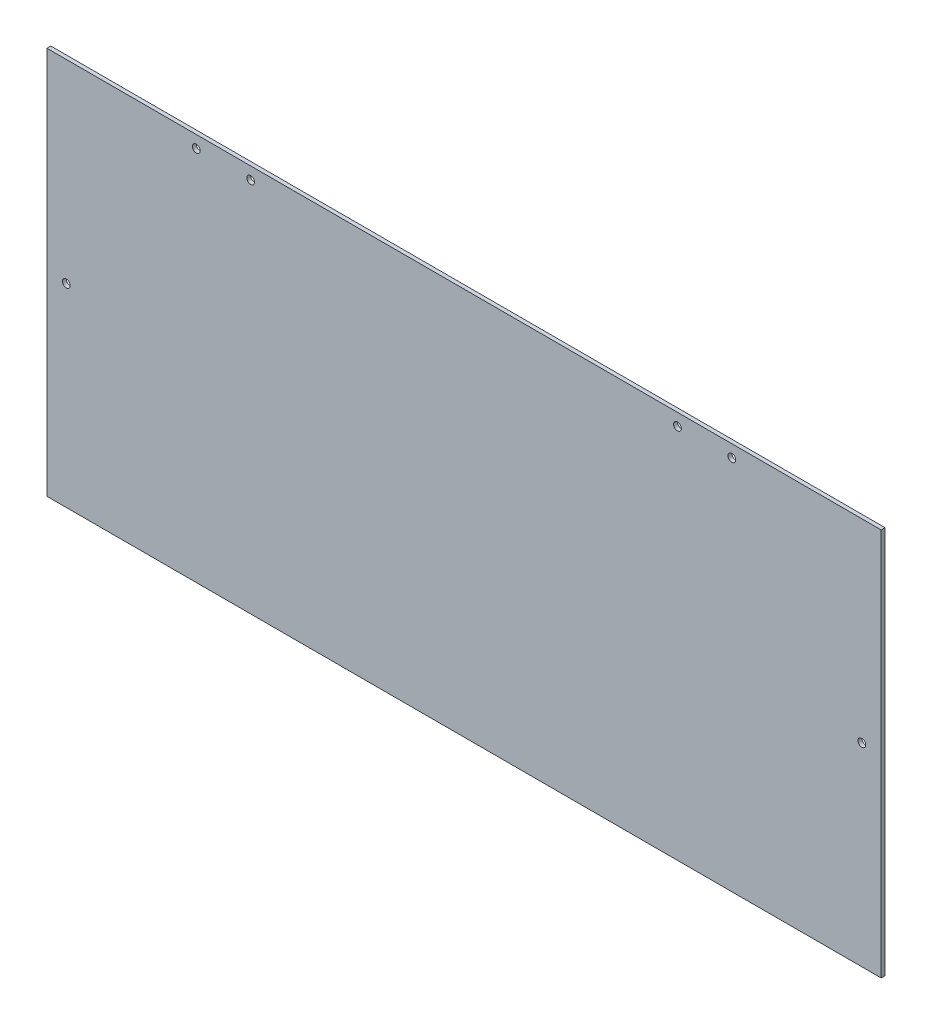
SolidWorks part; units mm, degrees
ref_plane "前视基准面" through (0, 0, 0) normal (0, 0, 1) x (1, 0, 0)
ref_plane "上视基准面" through (0, 0, 0) normal (0, 1, 0) x (1, 0, 0)
ref_plane "右视基准面" through (0, 0, 0) normal (1, 0, 0) x (0, 0, -1)
sketch "草图1" plane through (0, 0, 0) normal (0, 0, 1) x (1, 0, 0)
  line L1 (0, 0) -> (430, 0)
  line L2 (0, 0) -> (0, -200)
  line L3 (0, -200) -> (430, -200)
  line L4 (430, 0) -> (430, -200)
  line L12 (215, 0) -> (215, -200) construction
  line L13 (77, -6.3) -> (105, -6.3) construction
  circle A0 centre (10, -100) radius 2
  circle A1 centre (420, -100) radius 2
  circle A2 centre (77, -6.3) radius 2
  circle A3 centre (105, -6.3) radius 2
  circle A4 centre (325, -6.3) radius 2
  circle A5 centre (353, -6.3) radius 2
  dimension "D4" = 10
  dimension "D6" = 4
  dimension "D7" = 4
  dimension "D1" = 200
  dimension "D2" = 430
  dimension "D3" = 28
  dimension "D5" = 10
  dimension "D8" = 6.3
  dimension "D9" = 220
extrude "凸台-拉伸1" add sketch "草图1" along normal blind 2
